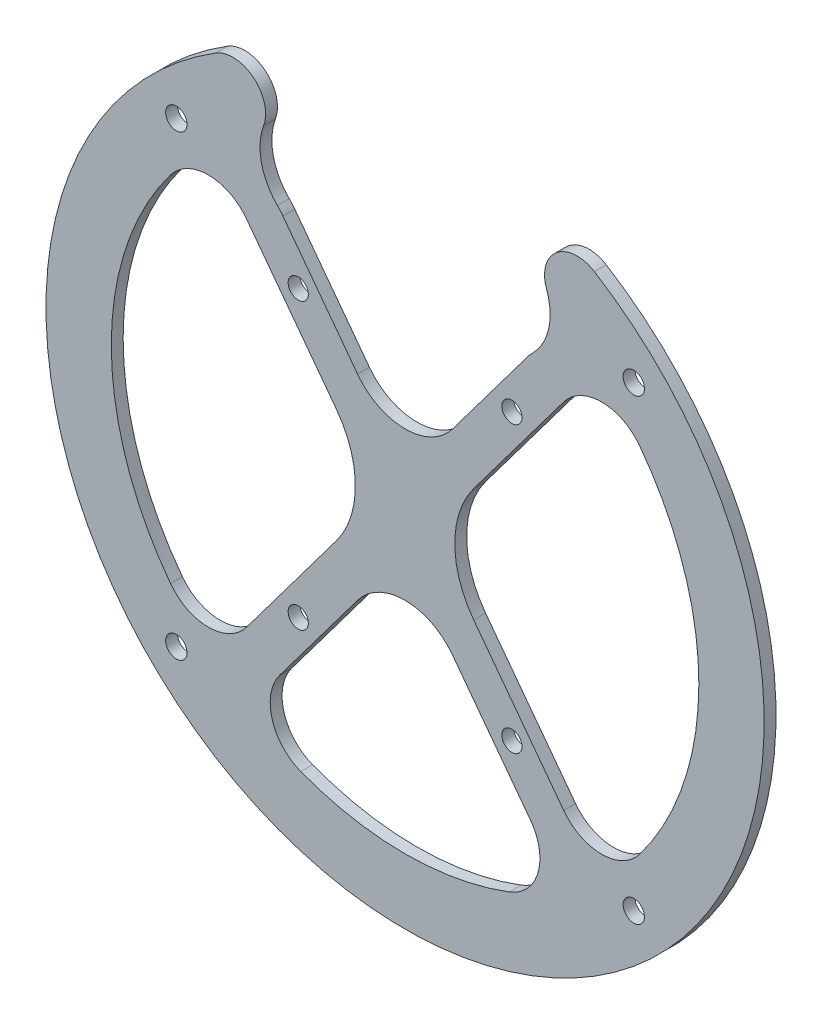
SolidWorks part; units mm, degrees
ref_plane "前视基准面" through (0, 0, 0) normal (0, 0, 1) x (1, 0, 0)
ref_plane "上视基准面" through (0, 0, 0) normal (0, 1, 0) x (1, 0, 0)
ref_plane "右视基准面" through (0, 0, 0) normal (1, 0, 0) x (0, 0, -1)
other "Configuration Table"
sketch "草图1" plane through (0, 0, 0) normal (0, 0, 1) x (1, 0, 0)
  line L0 (0, 54.5) -> (0, -54.5) construction
  line L1 (-54.5, 0) -> (59.8557, 0) construction
  line L2 (38.5373, 38.5373) -> (0, 0)
  circle A0 centre (0, 0) radius 54.5
  circle A1 centre (38.5373, 38.5373) radius 1.8
  circle A5 centre (0, 0) radius 60.5
  circle A6 centre (38.5373, -38.5373) radius 1.8
  circle A7 centre (-38.5373, -38.5373) radius 1.8
  circle A8 centre (-38.5373, 38.5373) radius 1.8
  point P17 (29.9279, 8.7951)
  point P18 (0, 0)
  dimension "D1" = 109
  dimension "D2" = 3.6
  dimension "D4" = 6
  dimension "D5" = 45
  dimension "D6" = 90
  dimension "D3" = 4
extrude "凸台-拉伸1" add sketch "草图1" along normal blind 2 contours A8 A0 A7 A6 A1 | A5 A8 A0 A1 A6 A7
sketch "草图2" plane through (0, 0, 2) normal (0, 0, 1) x (1, 0, 0)
  line L0 (0, 0) -> (42.78, 42.78) construction
  line L1 (0, 60.5) -> (0, -60.5) construction
  line L2 (26.8257, 41.6009) -> (0, 5.8333)
  line L3 (-18, 24) -> (18, 24) construction
  line L4 (-18, 24) -> (-18, -24) construction
  line L5 (-18, -24) -> (18, -24) construction
  line L6 (18, 24) -> (18, -24) construction
  line L7 (-18, 24) -> (18, -24) construction
  line L8 (-18, -24) -> (18, 24) construction
  line L9 (0, 5.8333) -> (-26.8257, 41.6009)
  line L10 (-60.5, 0) -> (60.5, 0) construction
  line L11 (26.8257, -41.6009) -> (0, -5.8333)
  line L12 (0, -5.8333) -> (-26.8257, -41.6009)
  line L13 (-32.4257, 37.4009) -> (-4.375, 0)
  line L14 (-4.375, 0) -> (-32.4257, -37.4009)
  line L15 (4.375, 0) -> (32.4257, -37.4009)
  line L16 (32.4257, 37.4009) -> (4.375, 0)
  circle A0 centre (0, 0) radius 60.5 construction
  circle A1 centre (0, 0) radius 60.5
  circle A2 centre (18, 24) radius 1.7
  circle A3 centre (-18, 24) radius 1.7
  circle A4 centre (18, -24) radius 1.7
  circle A5 centre (-18, -24) radius 1.7
  circle A10 centre (0, 0) radius 49.5
  circle A11 centre (0, 0) radius 33.5
  dimension "D4" = 3.4
  dimension "D5" = 3.5
  dimension "D6" = 11
  dimension "D7" = 16
  dimension "D8" = 3.5
  dimension "D1" = 45
  dimension "D2" = 36
  dimension "D3" = 48
extrude "切除-拉伸1" cut sketch "草图2" against normal blind 2 contours L13 A11 L14 | A11 L13 A10 L14 | A11 L2 A10 L9 | L2 A11 L9 | A11 L15 A10 L16 | L15 A11 L16 | A11 L12 A10 L11 | L12 A11 L11 | A2 | A3 | A5 | A4
fillet "圆角2" radius 16 2 edges at (4.375, 0, 1) (-4.375, 0, 1)
fillet "圆角3" radius 10 2 edges at (0, -5.8333, 1) (0, 5.8333, 1)
fillet "圆角4" radius 8 4 edges at (-26.8257, -41.6009, 1) (26.8257, -41.6009, 1) (26.8257, 41.6009, 1) (-26.8257, 41.6009, 1)
fillet "圆角5" radius 8 4 edges at (-32.4257, -37.4009, 1) (-32.4257, 37.4009, 1) (32.4257, -37.4009, 1) (32.4257, 37.4009, 1)
sketch "草图3" plane through (0, 0, 2) normal (0, 0, 1) x (1, 0, 0)
  line L0 (0, 0) -> (0, 60.5) construction
  line L1 (21.1249, 33.9998) -> (29, 41.2333)
  line L2 (-21.1249, 33.9998) -> (-29, 41.2333)
  arc A0 (39.5104, -29.8191) -> (39.5104, 29.8191) centre (0, 0) ccw construction
  circle A1 centre (0, 0) radius 60.5
  circle A2 centre (0, 0) radius 60.5
  arc A3 (39.5104, -29.8191) -> (39.5104, 29.8191) centre (0, 0) ccw
  circle A4 centre (-29, 46.7333) radius 5.5
  circle A5 centre (29, 46.7333) radius 5.5
  circle A6 centre (0, 0) radius 49.5
  arc A7 (17.5634, 46.2793) -> (-17.5634, 46.2793) centre (0, 0) ccw construction
  arc A8 (17.5634, 46.2793) -> (-17.5634, 46.2793) centre (0, 0) ccw
  circle M24 centre (0, 0) radius 60.5
  arc M31 (-17.5634, 46.2793) -> (17.5634, 46.2793) centre (0, 0) cw
  arc M32 (17.5634, 46.2793) -> (21.1249, 33.9998) centre (14.7249, 38.7998) cw
  arc M36 (-21.1249, 33.9998) -> (-17.5634, 46.2793) centre (-14.7249, 38.7998) cw
  dimension "D2" = 58
  dimension "D1" = 0
extrude "切除-拉伸4" cut sketch "草图3" against normal blind 10 contours A6 L2 M36 | L0 A4 A6 M31 M24 | L0 A8 A6 A5 A2 | L1 A6 M32
fillet "圆角7" radius 10 2 edges at (21.1249, 33.9998, 1) (-21.1249, 33.9998, 1)
fillet "圆角8" radius 10 2 edges at (28.3136, 40.6028, 1) (-28.3136, 40.6028, 1)
